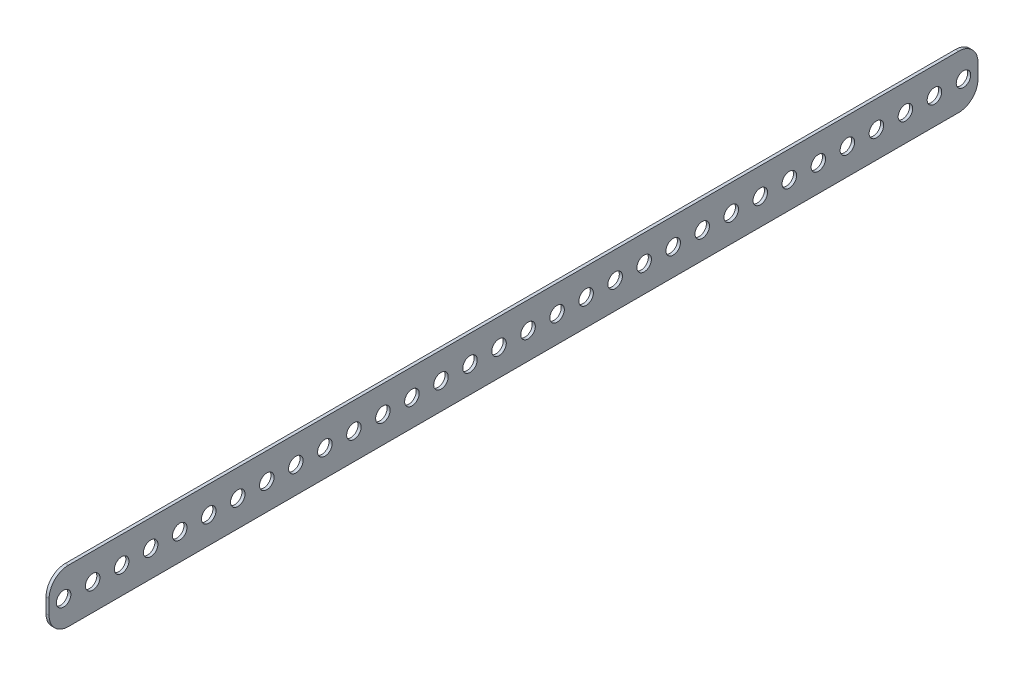
SolidWorks part; units mm, degrees
ref_plane "Front Plane" through (0, 0, 0) normal (0, 0, 1) x (1, 0, 0)
ref_plane "Top Plane" through (0, 0, 0) normal (0, 1, 0) x (1, 0, 0)
ref_plane "Right Plane" through (0, 0, 0) normal (1, 0, 0) x (0, 0, -1)
sketch "Sketch1" plane through (0, 0, 0) normal (0, 0, 1) x (1, 0, 0)
  line L1 (2.032, 0) -> (0, 0)
  line L2 (2.032, 0) -> (2.032, 34.925)
  line L3 (2.032, 34.925) -> (0, 34.925)
  line L4 (0, 0) -> (0, 34.925)
  dimension "D2" = 2.032
  dimension "D1" = 34.925
extrude "Boss-Extrude1" add sketch "Sketch1" along normal mid plane 609.6
sketch "Sketch2" plane through (0, 0, 0) normal (-1, 0, 0) x (0, 0, 1)
  line L0 (295.275, 17.4625) -> (276.225, 17.4625) construction
  line L1 (295.275, 17.4625) -> (304.8, 17.4625) construction
  line L2 (304.8, 0) -> (304.8, 34.925) construction
  circle A0 centre (295.275, 17.4625) radius 4.7625
  dimension "D1" = 9.525
  dimension "D2" = 19.05
  dimension "D3" = 9.525
extrude "Cut-Extrude1" cut sketch "Sketch2" against normal up to next
pattern_linear "LPattern1" count 32 spacing 19.05 along (0, 0, -1) of "Cut-Extrude1"
sketch "Sketch3" plane through (0, 0, 0) normal (1, 0, 0) x (0, 0, -1)
  line L0 (-304.8, 0) -> (-304.8, 34.925) construction
  point P0 (-95.25, 16.9798)
  dimension "D1" = 209.55
ref_plane "Plane1" through (0, 0, 95.25) normal (0, 0, 1) x (1, 0, 0)
sketch "Sketch4" plane through (0, 0, 95.25) normal (0, 0, 1) x (1, 0, 0)
  line L4 (0, 34.925) -> (0, 0)
  line L5 (2.032, 34.925) -> (0, 34.925)
  line L6 (2.032, 0) -> (2.032, 34.925)
  line L7 (0, 0) -> (2.032, 0)
  line L8 (0, 34.925) -> (0, 0)
  line L9 (2.032, 34.925) -> (0, 34.925)
  line L10 (2.032, 0) -> (2.032, 34.925)
  line L11 (0, 0) -> (2.032, 0)
  dimension "D1" = 0
fillet "Fillet1" radius 12.7 4 edges at (1.016, 34.925, -304.8) (1.016, 0, -304.8) (1.016, 0, 304.8) (1.016, 34.925, 304.8)
equation "\"D3@Sketch2\" = \"D2@Sketch2\" / 2"
equation "\"D3@LPattern1\" = \"D2@Sketch2\""
equation "\"D1@LPattern1\" = \"D1@Boss-Extrude1\" / \"D2@Sketch2\""
